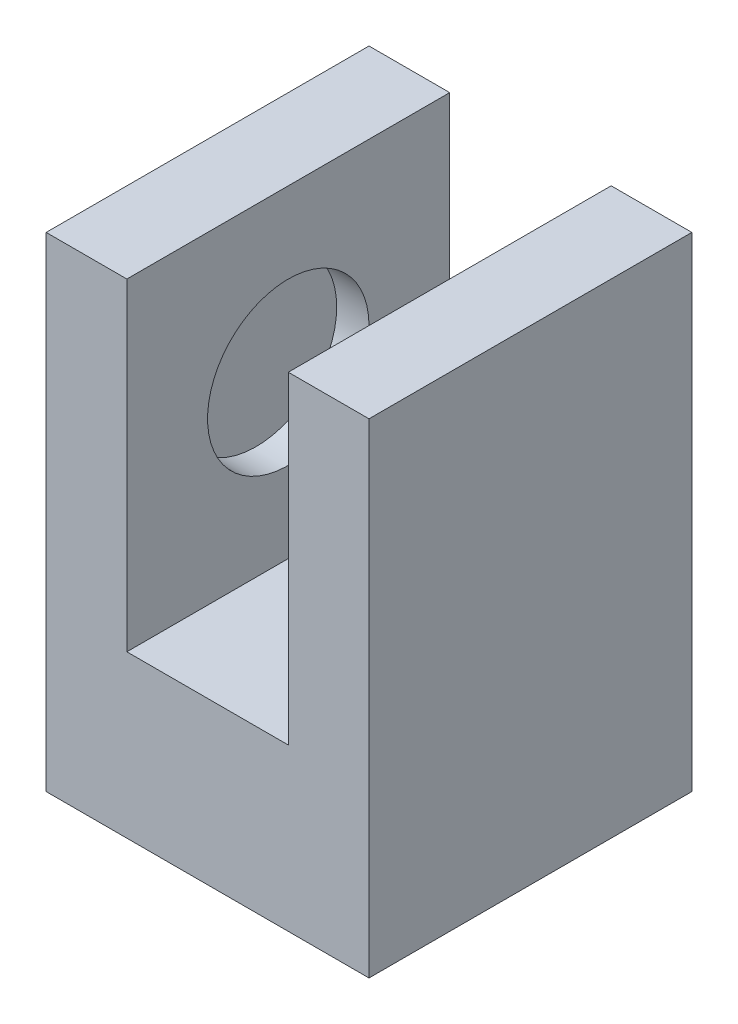
SolidWorks part; units mm, degrees
material "普通碳钢"
ref_plane "前视基准面" through (0, 0, 0) normal (0, 0, 1) x (1, 0, 0)
ref_plane "上视基准面" through (0, 0, 0) normal (0, 1, 0) x (1, 0, 0)
ref_plane "右视基准面" through (0, 0, 0) normal (1, 0, 0) x (0, 0, -1)
sketch "草图2" plane through (0, 0, 0) normal (0, 1, 0) x (1, 0, 0)
  line L0 (-50, -50) -> (50, -50)
  line L5 (0, 0) -> (50, 0) construction
  line L6 (0, 0) -> (0, 50) construction
  line L7 (-50, 50) -> (50, 50)
  line L8 (50, -50) -> (50, 50)
  line L9 (-50, -50) -> (-50, 50)
  point P9 (0, -50)
  dimension "D1" = 50
  dimension "D2" = 50
extrude "凸台-拉伸1" add sketch "草图2" along normal blind 50 and the other way blind 100
sketch "草图3" plane through (0, 50, 0) normal (0, 1, 0) x (1, 0, 0)
  line L0 (-25, 50) -> (-25, -50)
  line L1 (50, 50) -> (-50, 50) construction
  line L2 (-50, -50) -> (50, -50) construction
  line L3 (-25, -50) -> (25, -50)
  line L4 (25, -50) -> (25, 50)
  line L5 (25, 50) -> (-25, 50)
  dimension "D1" = 25
  dimension "D2" = 25
extrude "切除-拉伸1" cut sketch "草图3" against normal blind 100
sketch "草图4" plane through (-25, 0, 0) normal (1, 0, 0) x (0, 0, -1)
  circle A0 centre (0, 0) radius 25
  dimension "D1" = 50
extrude "切除-拉伸2" cut sketch "草图4" against normal blind 10
sketch "草图5" plane through (25, 0, 0) normal (-1, 0, 0) x (0, 0, 1)
  circle A0 centre (0, 0) radius 25
  dimension "D1" = 50
extrude "切除-拉伸3" cut sketch "草图5" against normal blind 10
